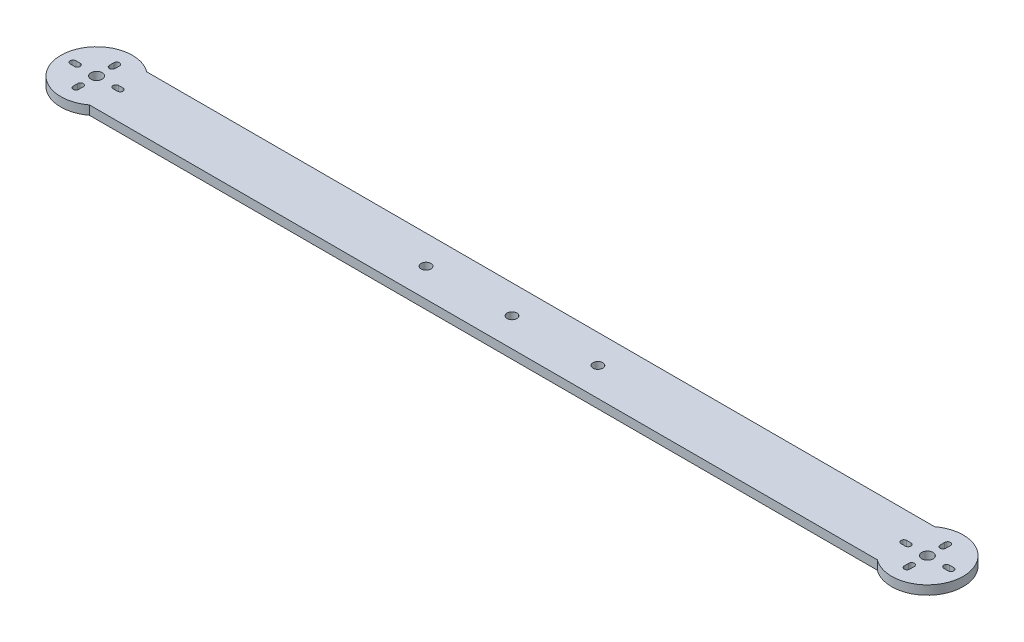
SolidWorks part; units mm, degrees
ref_plane "Front Plane" through (0, 0, 0) normal (0, 0, 1) x (1, 0, 0)
ref_plane "Top Plane" through (0, 0, 0) normal (0, 1, 0) x (1, 0, 0)
ref_plane "Right Plane" through (0, 0, 0) normal (1, 0, 0) x (0, 0, -1)
sketch "Sketch1" plane through (0, 0, 0) normal (0, 1, 0) x (1, 0, 0)
  line L0 (0, 12.7) -> (0, -12.7) construction
  line L1 (-174.625, 12.7) -> (174.625, 12.7)
  line L3 (-174.625, -12.7) -> (174.625, -12.7)
  arc A0 (-174.625, 12.7) -> (-174.625, -12.7) centre (-184.15, 0) ccw
  arc A1 (174.625, -12.7) -> (174.625, 12.7) centre (184.15, 0) ccw
  point P8 (0, 12.7)
  point P12 (0, 0)
  dimension "D3" = 31.75
  dimension "D4" = 31.75
extrude "Boss-Extrude1" add sketch "Sketch1" along normal blind 4
sketch "Sketch2" plane through (0, 4, 0) normal (0, 1, 0) x (1, 0, 0)
  line L0 (173.6914, 0) -> (175.6086, 0) construction
  line L1 (173.6914, 1.25) -> (175.6086, 1.25)
  line L2 (173.6914, -1.25) -> (175.6086, -1.25)
  line L3 (184.15, 0) -> (184.15, 3.2374) construction
  line L4 (194.6086, 0) -> (192.6914, 0) construction
  line L5 (194.6086, 1.25) -> (192.6914, 1.25)
  line L6 (194.6086, -1.25) -> (192.6914, -1.25)
  line L7 (184.15, 8.9209) -> (184.15, 6.921) construction
  line L8 (185.4, 8.9209) -> (185.4, 6.921)
  line L9 (182.9, 8.9209) -> (182.9, 6.921)
  line L10 (184.1914, -9.079) -> (184.1914, -7.079) construction
  line L11 (185.4414, -9.079) -> (185.4414, -7.079)
  line L12 (182.9414, -9.079) -> (182.9414, -7.079)
  line L13 (0, 0) -> (184.15, 0) construction
  line L14 (0, 0) -> (0, 12.7) construction
  line L15 (174.625, 12.7) -> (-174.625, 12.7) construction
  line L16 (-184.15, 0) -> (-184.15, 3.2374) construction
  line L17 (-184.1914, -9.079) -> (-184.1914, -7.079) construction
  line L18 (-185.4414, -9.079) -> (-185.4414, -7.079)
  line L19 (-182.9414, -9.079) -> (-182.9414, -7.079)
  line L20 (-184.15, 8.9209) -> (-184.15, 6.921) construction
  line L21 (-185.4, 8.9209) -> (-185.4, 6.921)
  line L22 (-182.9, 8.9209) -> (-182.9, 6.921)
  line L23 (-194.6086, 0) -> (-192.6914, 0) construction
  line L24 (-194.6086, 1.25) -> (-192.6914, 1.25)
  line L25 (-194.6086, -1.25) -> (-192.6914, -1.25)
  line L26 (-173.6914, 0) -> (-175.6086, 0) construction
  line L27 (-173.6914, 1.25) -> (-175.6086, 1.25)
  line L28 (-173.6914, -1.25) -> (-175.6086, -1.25)
  circle A0 centre (184.15, 0) radius 2.5
  arc A1 (173.6914, 1.25) -> (173.6914, -1.25) centre (173.6914, 0) ccw
  arc A2 (175.6086, -1.25) -> (175.6086, 1.25) centre (175.6086, 0) ccw
  arc A3 (194.6086, 1.25) -> (194.6086, -1.25) centre (194.6086, 0) cw
  arc A4 (192.6914, -1.25) -> (192.6914, 1.25) centre (192.6914, 0) cw
  arc A5 (185.4, 8.9209) -> (182.9, 8.9209) centre (184.15, 8.9209) ccw
  arc A6 (182.9, 6.921) -> (185.4, 6.921) centre (184.15, 6.921) ccw
  arc A7 (185.4414, -9.079) -> (182.9414, -9.079) centre (184.1914, -9.079) cw
  arc A8 (182.9414, -7.079) -> (185.4414, -7.079) centre (184.1914, -7.079) cw
  circle A9 centre (-184.15, 0) radius 2.5
  arc A10 (-185.4414, -9.079) -> (-182.9414, -9.079) centre (-184.1914, -9.079) ccw
  arc A11 (-182.9414, -7.079) -> (-185.4414, -7.079) centre (-184.1914, -7.079) ccw
  arc A12 (-185.4, 8.9209) -> (-182.9, 8.9209) centre (-184.15, 8.9209) cw
  arc A13 (-182.9, 6.921) -> (-185.4, 6.921) centre (-184.15, 6.921) cw
  arc A14 (-194.6086, 1.25) -> (-194.6086, -1.25) centre (-194.6086, 0) ccw
  arc A15 (-192.6914, -1.25) -> (-192.6914, 1.25) centre (-192.6914, 0) ccw
  arc A16 (-173.6914, 1.25) -> (-173.6914, -1.25) centre (-173.6914, 0) cw
  arc A17 (-175.6086, -1.25) -> (-175.6086, 1.25) centre (-175.6086, 0) cw
  point P4 (174.65, 0)
  point P12 (193.65, 0)
  point P19 (184.15, 7.921)
  point P26 (184.1914, -8.079)
  point P41 (-184.1914, -8.079)
  point P48 (-184.15, 7.921)
  point P55 (-193.65, 0)
  point P62 (-174.65, 0)
  dimension "D1" = 16
  dimension "D2" = 19
  dimension "D3" = 184.15
extrude "Cut-Extrude1" cut sketch "Sketch2" against normal through all
sketch "Sketch3" plane through (0, 4, 0) normal (0, 1, 0) x (1, 0, 0)
  circle A0 centre (0, 0) radius 2.159
  circle A1 centre (38.1, 0) radius 2.159
  circle A2 centre (-38.1, 0) radius 2.159
  dimension "D1" = 38.1
  dimension "D3" = 4.318
  dimension "D4" = 4.318
  dimension "D5" = 4.318
  dimension "D2" = 38.1
extrude "Cut-Extrude2" cut sketch "Sketch3" against normal through all
